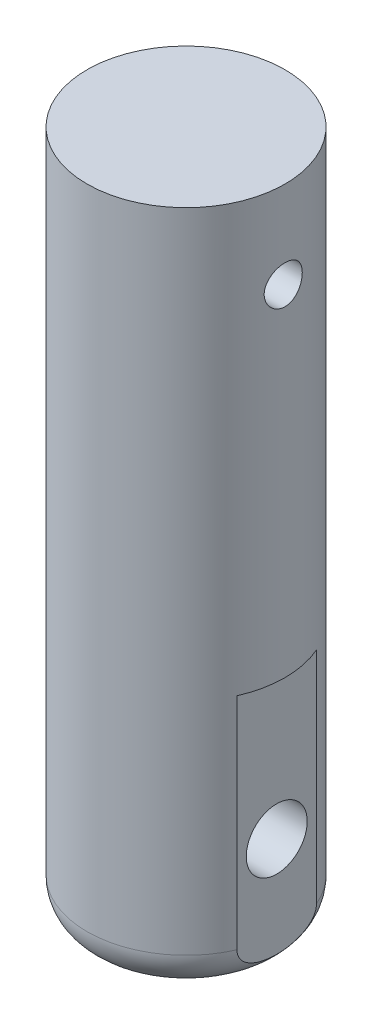
SolidWorks part; units mm, degrees
ref_plane "Спереди" through (0, 0, 0) normal (0, 0, 1) x (1, 0, 0)
ref_plane "Сверху" through (0, 0, 0) normal (0, 1, 0) x (1, 0, 0)
ref_plane "Справа" through (0, 0, 0) normal (1, 0, 0) x (0, 0, -1)
sketch "Эскиз1" plane through (0, 0, 0) normal (0, 1, 0) x (1, 0, 0)
  circle A0 centre (0.9593, 0) radius 13
  dimension "D1" = 26
extrude "Вытянуть1" add sketch "Эскиз1" along normal blind 90
fillet "Скругление1" radius 5 1 edges at (0.9593, 0, 13)
sketch "Эскиз3" plane through (0, 0, 0) normal (1, 0, 0) x (0, 0, -1)
  line L0 (0, 0) -> (0, 31.7007) construction
  circle A0 centre (0, 15) radius 4
  dimension "D1" = 8
  dimension "D2" = 15
extrude "Вытянуть2" cut sketch "Эскиз3" against normal mid plane 40
sketch "Эскиз4" plane through (0, 0, 0) normal (0, 0, 1) x (1, 0, 0)
  line L0 (1.0539, 0) -> (1.0539, 35.243) construction
  line L2 (-16.3956, 33.8821) -> (-10.7574, 33.8821)
  line L3 (-10.7574, 33.8821) -> (-10.7574, -0.9198)
  line L4 (-10.7574, -0.9198) -> (-16.3956, -0.9198)
  line L5 (-16.3956, -0.9198) -> (-16.3956, 33.8821)
  line L6 (12.8651, -0.9198) -> (18.5034, -0.9198)
  line L7 (12.8651, 33.8821) -> (12.8651, -0.9198)
  line L8 (18.5034, 33.8821) -> (12.8651, 33.8821)
  line L9 (18.5034, 33.8821) -> (18.5034, -0.9198)
  dimension "D1" = 18.5034
  dimension "D2" = 12.8651
  dimension "D3" = 16.3956
  dimension "D4" = 33.8821
  dimension "D5" = 0.9198
extrude "Вытянуть3" cut sketch "Эскиз4" against normal mid plane 45
sketch "Эскиз5" plane through (0, 0, 0) normal (1, 0, 0) x (0, 0, -1)
  circle A0 centre (0, 78.5596) radius 2.5
  dimension "D1" = 5
extrude "Вырез-Вытянуть1" cut sketch "Эскиз5" against normal mid plane 110
